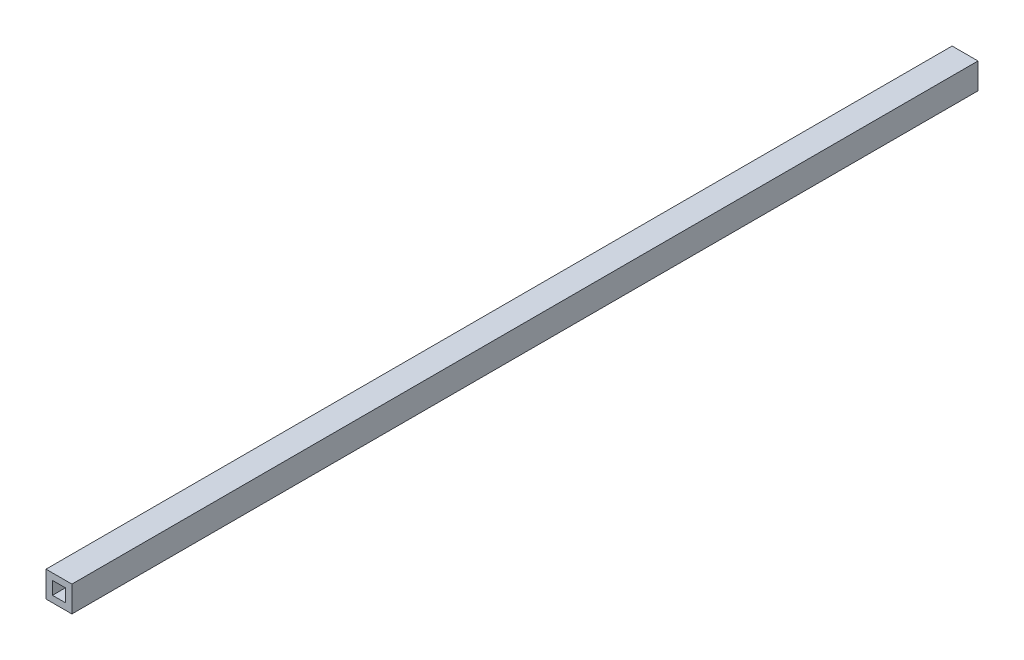
SolidWorks part; units mm, degrees
material "6063-O"
ref_plane "Front Plane" through (0, 0, 0) normal (0, 0, 1) x (1, 0, 0)
ref_plane "Top Plane" through (0, 0, 0) normal (0, 1, 0) x (1, 0, 0)
ref_plane "Right Plane" through (0, 0, 0) normal (1, 0, 0) x (0, 0, -1)
sketch "Sketch1" plane through (0, 0, 0) normal (0, 0, 1) x (1, 0, 0)
  line L1 (-10, -10) -> (10, -10)
  line L2 (-10, -10) -> (-10, 10)
  line L3 (-10, 10) -> (10, 10)
  line L4 (10, -10) -> (10, 10)
  line L5 (-10, -10) -> (10, 10) construction
  line L6 (-10, 10) -> (10, -10) construction
  point P0 (0, 0)
  dimension "D1" = 20
extrude "Extrude-Thin1" add sketch "Sketch1" along normal blind 700 thin thin type one direction reverse wall 5
